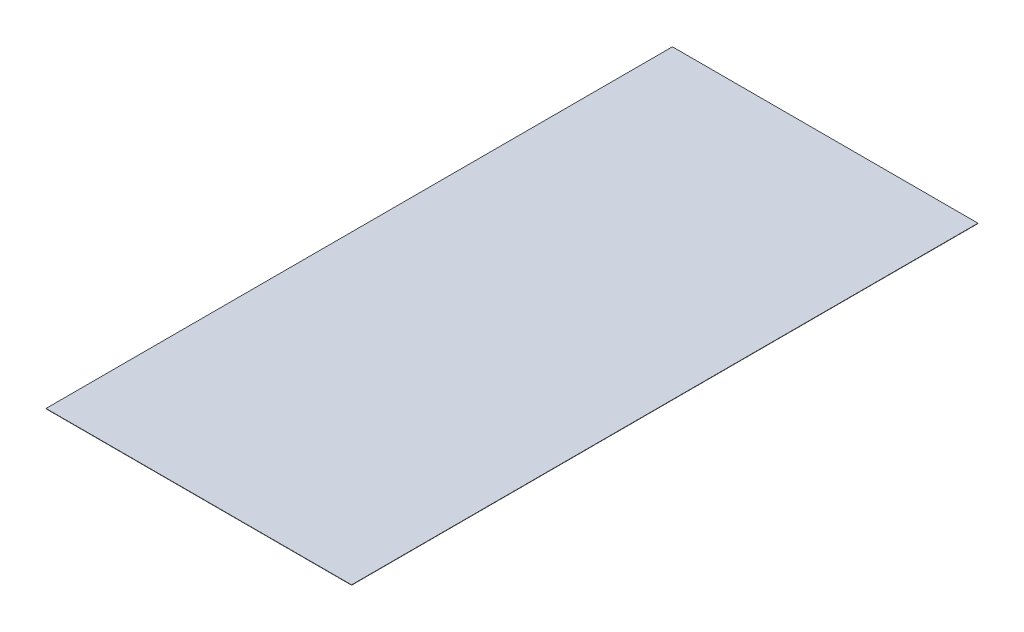
SolidWorks part; units mm, degrees
ref_plane "Спереди" through (0, 0, 0) normal (0, 0, 1) x (1, 0, 0)
ref_plane "Сверху" through (0, 0, 0) normal (0, 1, 0) x (1, 0, 0)
ref_plane "Справа" through (0, 0, 0) normal (1, 0, 0) x (0, 0, -1)
other "Configuration Table"
sketch "Эскиз1" plane through (0, 0, 0) normal (0, 1, 0) x (1, 0, 0)
  line L1 (500, 1025) -> (-500, 1025)
  line L2 (500, 1025) -> (500, -1025)
  line L3 (500, -1025) -> (-500, -1025)
  line L4 (-500, 1025) -> (-500, -1025)
  line L5 (500, 1025) -> (-500, -1025) construction
  line L6 (500, -1025) -> (-500, 1025) construction
  point P0 (0, 0)
extrude "Бобышка-Вытянуть1" add sketch "Эскиз1" along normal blind 1
